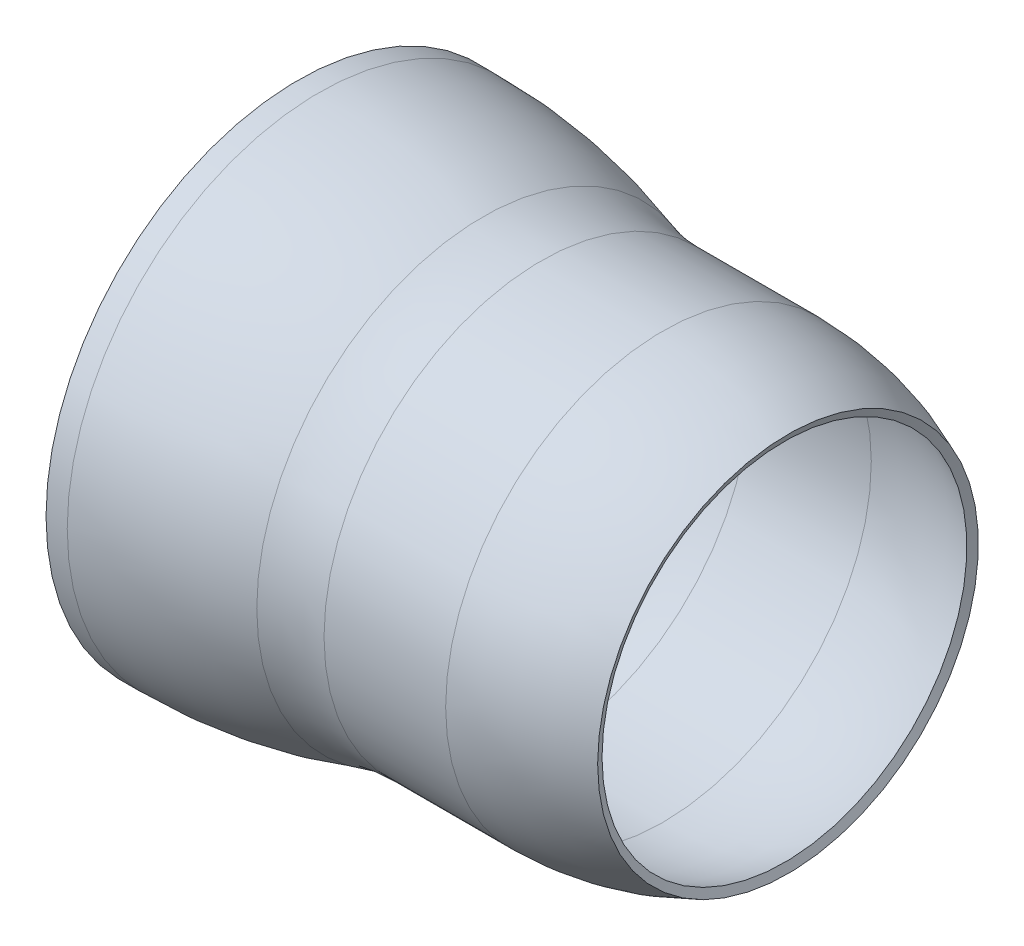
SolidWorks part; units mm, degrees
ref_plane "Front Plane" through (0, 0, 0) normal (0, 0, 1) x (1, 0, 0)
ref_plane "Top Plane" through (0, 0, 0) normal (0, 1, 0) x (1, 0, 0)
ref_plane "Right Plane" through (0, 0, 0) normal (1, 0, 0) x (0, 0, -1)
sketch "Sketch1" plane through (0, 0, 0) normal (0, 0, 1) x (1, 0, 0)
  line L0 (0, 0) -> (0, 140)
  line L1 (0, 140) -> (12.209, 140)
  line L2 (0, 0) -> (280, 0) construction
  line L3 (280, 0) -> (280, 105)
  line L5 (140, 120) -> (210, 120)
  line L6 (0, 145) -> (12.209, 145)
  line L7 (140, 125) -> (210, 125)
  line L8 (0, 145) -> (0, 140)
  line L9 (280, 105) -> (282.0488, 109.561)
  arc A0 (12.209, 140) -> (105, 125.4777) centre (12.209, -163.7076) cw
  arc A2 (140, 120) -> (105, 125.4777) centre (140, 234.556) cw
  arc A3 (210, 120) -> (280, 105) centre (210, -50.8333) cw
  arc A4 (12.209, 145) -> (106.5276, 130.2386) centre (12.209, -163.7076) cw
  arc A5 (140, 125) -> (106.5276, 130.2386) centre (140, 234.556) cw
  arc A6 (210, 125) -> (282.0488, 109.561) centre (210, -50.8333) cw
  dimension "D1" = 140
  dimension "D2" = 105
  dimension "D3" = 280
  dimension "D5" = 12.209
  dimension "D6" = 175
  dimension "D7" = 140
  dimension "D4" = 120
  dimension "D8" = 70
  dimension "D9" = 5
revolve "Revolve1" add sketch "Sketch1" angle 360 about L2
equation "\"ThrusterDim\"= 140mm"
equation "\"D1@Sketch1\"=\"ThrusterDim\""
equation "\"D2@Sketch1\"=.75 * \"ThrusterDim\""
equation "\"D3@Sketch1\"=2 * \"ThrusterDim\""
equation "\"D6@Sketch1\"=\"ThrusterDim\" * 1.25"
equation "\"D7@Sketch1\"=\"ThrusterDim\""
equation "\"D4@Sketch1\"=\"ThrusterDim\"* 0.85714286"
equation "\"hatchHoleDiameter\"= 600mm"
equation "\"hullThickness\"= 120mm"
equation "\"gasketHullInterconnectWidth\"= 100mm"
equation "\"collarThickness\"= 15"
equation "\"hatchTunnelLength\"=200"
equation "\"oRingDiameter\"=2"
equation "\"boltPatternRadiusInterconnect\"=500"
equation "\"interconnectBoltDiameter\"=30"
equation "\"hatchShaftDiameter\"=20"
equation "\"hatchMinima\"=50"
equation "\"hullDiameter\"=2000"
equation "\"hatchMaxima\"=180"
equation "\"bushingFlatHatch\"=15"
equation "\"hingePivotDiameter\"=20"
equation "\"handleWidth\"=250"
equation "\"handleHeight\"=160"
equation "\"handleThickness\"=25"
equation "\"FrameLength\"= 4300"
equation "\"FrameMidLength\"= 3000"
equation "\"TubeOD\"= 100"
equation "\"FrameBackFlat\"= 800"
equation "\"TubeWall\"=15"
equation "\"TopMemberAngle\"=120"
equation "\"FrameHight\"= 2500"
